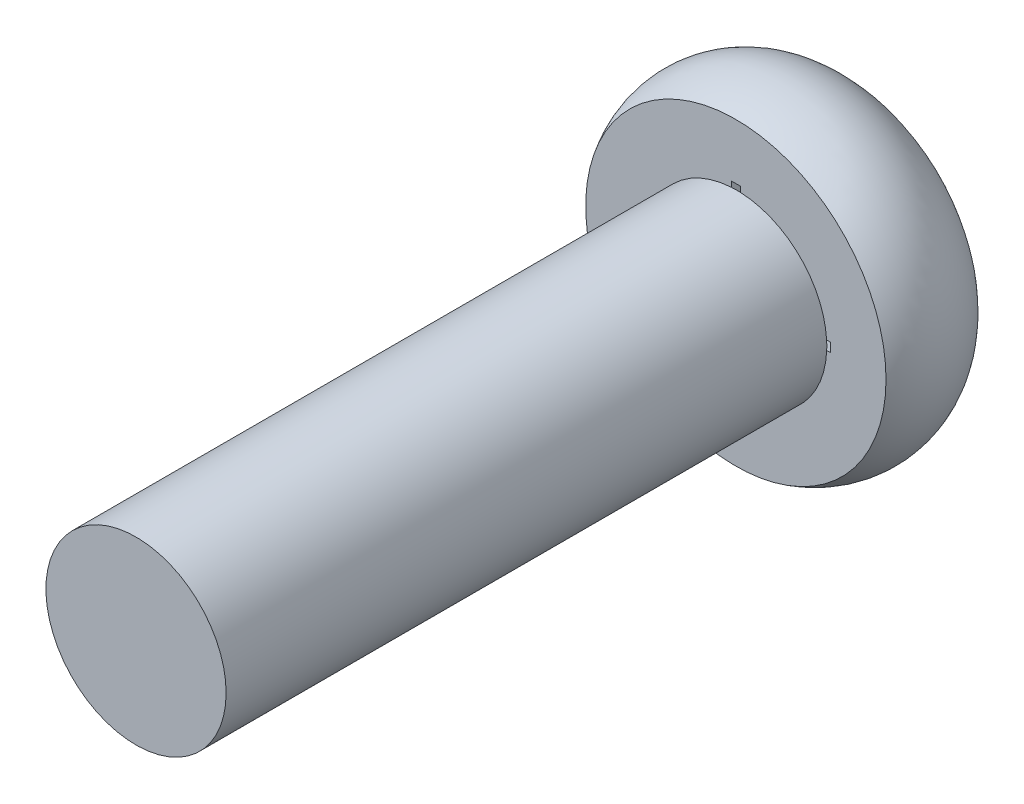
SolidWorks part; units mm, degrees
ref_plane "Front Plane" through (0, 0, 0) normal (0, 0, 1) x (1, 0, 0)
ref_plane "Top Plane" through (0, 0, 0) normal (0, 1, 0) x (1, 0, 0)
ref_plane "Right Plane" through (0, 0, 0) normal (1, 0, 0) x (0, 0, -1)
sketch "Sketch1" plane through (0, 0, 0) normal (0, 1, 0) x (1, 0, 0)
  line L0 (0, 0.6593) -> (0, 4.5218) construction
  line L3 (0, 0) -> (0, 2)
  line L4 (0, 0) -> (2.5, 0)
  line L5 (0, 2) -> (1.7983, 2)
  arc A0 (2.0735, 1.9174) -> (2.5, 0) centre (1.2961, 0.7384) cw
  arc A1 (2.0735, 1.9174) -> (1.7983, 2) centre (1.7983, 1.5) ccw
  dimension "D2" = 0.5
revolve "Revolve2" add sketch "Sketch1" angle 360 about L0
sketch "Sketch2" plane through (0, 0, -2) normal (0, 0, -1) x (-1, 0, 0)
  line L0 (0, 0) -> (2.5296, 0) construction
  line L1 (0, 0) -> (0, 1.7464) construction
  line L2 (0.5, -0.5) -> (2, -0.5)
  line L3 (-0.5, 2) -> (0.5, 2)
  line L4 (-0.5, 2) -> (-0.5, 0.5)
  line L5 (-0.5, -2) -> (0.5, -2)
  line L6 (0.5, 2) -> (0.5, 0.5)
  line L7 (0.5, 0.5) -> (2, 0.5)
  line L8 (0.5, -0.5) -> (0.5, -2)
  line L9 (-2, 0.5) -> (-0.5, 0.5)
  line L10 (-2, 0.5) -> (-2, -0.5)
  line L11 (-2, -0.5) -> (-0.5, -0.5)
  line L12 (2, 0.5) -> (2, -0.5)
  line L15 (-0.5, -0.5) -> (-0.5, -2)
  point P4 (0, 0)
  point P12 (0, 0)
  dimension "D1" = 0.5
  dimension "D2" = 2
  dimension "D3" = 2
  dimension "D4" = 2
  dimension "D5" = 0.5
  dimension "D6" = 0.5
  dimension "D7" = 0.5
  dimension "D8" = 0.5
extrude "Cut-Extrude1" cut sketch "Sketch2" against normal blind 2 draft 12
sketch "Sketch3" plane through (0, 0, 0) normal (0, 0, 1) x (1, 0, 0)
  circle A0 centre (0.0136, -0.0136) radius 1.5
extrude "Boss-Extrude1" add sketch "Sketch3" along normal blind 10
cosmetic thread "Cosmetic Thread2" parameters "D2"=2.439
